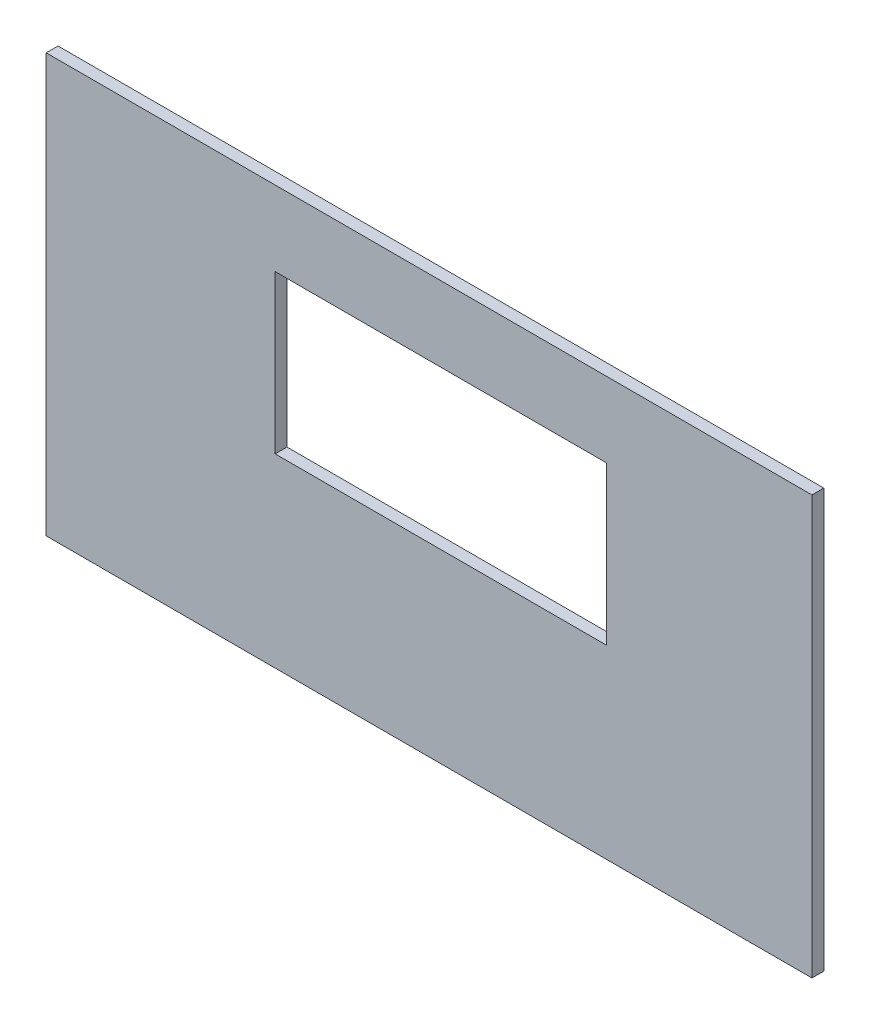
SolidWorks part; units mm, degrees
ref_plane "Front Plane" through (0, 0, 0) normal (0, 0, 1) x (1, 0, 0)
ref_plane "Top Plane" through (0, 0, 0) normal (0, 1, 0) x (1, 0, 0)
ref_plane "Right Plane" through (0, 0, 0) normal (1, 0, 0) x (0, 0, -1)
sketch "Sketch1" plane through (0, 0, 0) normal (0, 0, 1) x (1, 0, 0)
  line L1 (0, 0) -> (194, 0)
  line L2 (0, 0) -> (0, 106)
  line L3 (0, 106) -> (194, 106)
  line L4 (194, 0) -> (194, 106)
  line L5 (58, 47) -> (142, 47)
  line L6 (58, 47) -> (58, 87)
  line L7 (58, 87) -> (142, 87)
  line L8 (142, 47) -> (142, 87)
  dimension "D1" = 58
  dimension "D2" = 142
  dimension "D3" = 194
  dimension "D4" = 47
  dimension "D5" = 87
  dimension "D6" = 106
extrude "Profile" add sketch "Sketch1" along normal blind 3
equation "\"Profile_Depth\" = 3mm"
equation "\"D1@Profile\" = \"Profile_Depth\""
equation "\"Profile_Sketch_1\" = 58mm"
equation "\"D1@Sketch1\" = \"Profile_Sketch_1\""
equation "\"Profile_Sketch_2\" = 142mm"
equation "\"D2@Sketch1\" = \"Profile_Sketch_2\""
equation "\"Profile_Sketch_3\" = 194mm"
equation "\"D3@Sketch1\" = \"Profile_Sketch_3\""
equation "\"Profile_Sketch_4\" = 47mm"
equation "\"D4@Sketch1\" = \"Profile_Sketch_4\""
equation "\"Profile_Sketch_5\" = 87mm"
equation "\"D5@Sketch1\" = \"Profile_Sketch_5\""
equation "\"Profile_Sketch_6\" = 106mm"
equation "\"D6@Sketch1\" = \"Profile_Sketch_6\""
equation "\"EnvelopeWidth\" = 194mm"
equation "\"EnvelopeHeight\" = 106mm"
